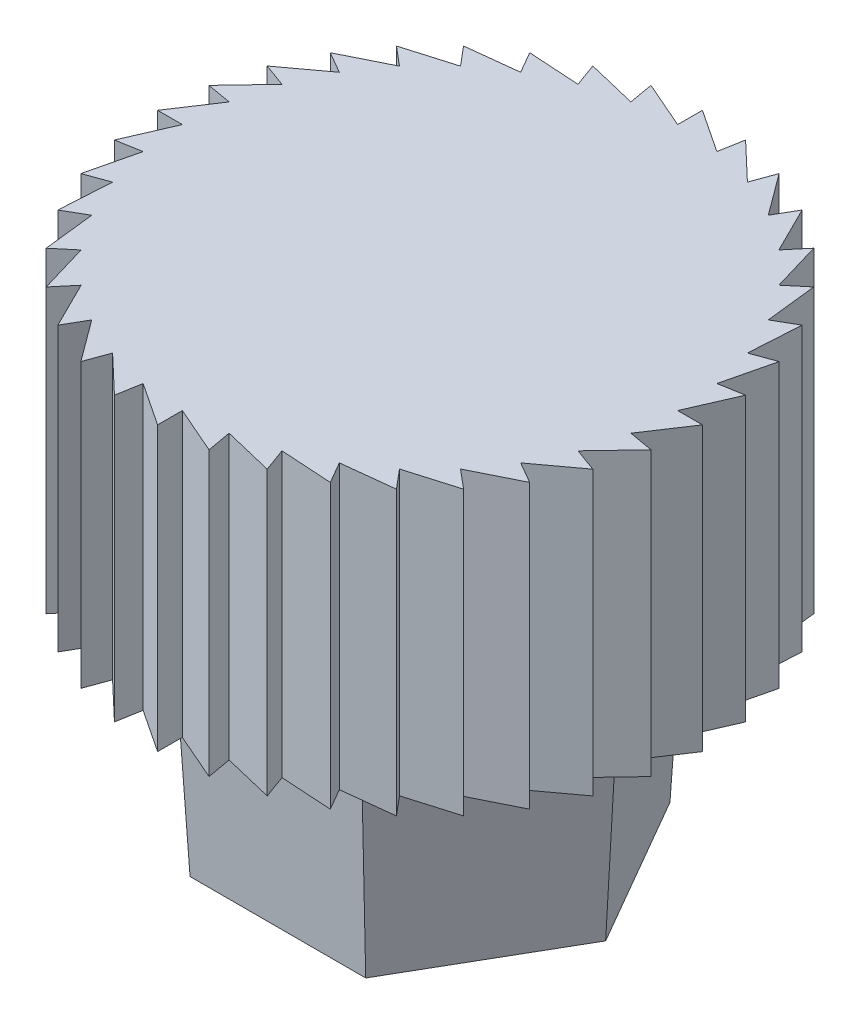
SolidWorks part; units mm, degrees
ref_plane "Front Plane" through (0, 0, 0) normal (0, 0, 1) x (1, 0, 0)
ref_plane "Top Plane" through (0, 0, 0) normal (0, 1, 0) x (1, 0, 0)
ref_plane "Right Plane" through (0, 0, 0) normal (1, 0, 0) x (0, 0, -1)
sketch "Sketch1" plane through (0, 0, 0) normal (0, 1, 0) x (1, 0, 0)
  line L1 (2.4826, 0) -> (1.2413, 2.15)
  line L2 (1.2413, 2.15) -> (-1.2413, 2.15)
  line L3 (-1.2413, 2.15) -> (-2.4826, 0)
  line L4 (-2.4826, 0) -> (-1.2413, -2.15)
  line L5 (-1.2413, -2.15) -> (1.2413, -2.15)
  line L6 (1.2413, -2.15) -> (2.4826, 0)
  circle A0 centre (0, 0) radius 2.15 construction
ref_plane "Plane1" through (0, 3, 0) normal (0, 1, 0) x (1, 0, 0)
sketch "Sketch2" plane through (0, 3, 0) normal (0, 1, 0) x (1, 0, 0)
  line L1 (2.6558, 0) -> (1.3279, 2.3)
  line L2 (1.3279, 2.3) -> (-1.3279, 2.3)
  line L3 (-1.3279, 2.3) -> (-2.6558, 0)
  line L4 (-2.6558, 0) -> (-1.3279, -2.3)
  line L5 (-1.3279, -2.3) -> (1.3279, -2.3)
  line L6 (1.3279, -2.3) -> (2.6558, 0)
  circle A0 centre (0, 0) radius 2.3 construction
loft "Loft1" add profiles "Sketch1", "Sketch2"
sketch "Sketch3" plane through (0, 3, 0) normal (0, 1, 0) x (1, 0, 0)
  line L0 (0, 0) -> (0, 3.9809) construction
  line L2 (0, 0) -> (0.7188, 4.0763) construction
  line L4 (0, 3.5) -> (0, 3.85)
  line L5 (0, 3.85) -> (0.6078, 3.4468)
  line L149 (0.6078, 3.4468) -> (0.6685, 3.7915)
  line L150 (0.6685, 3.7915) -> (1.1971, 3.2889)
  line L151 (1.1971, 3.2889) -> (1.3168, 3.6178)
  line L152 (1.3168, 3.6178) -> (1.75, 3.0311)
  line L153 (1.75, 3.0311) -> (1.925, 3.3342)
  line L154 (1.925, 3.3342) -> (2.2498, 2.6812)
  line L155 (2.2498, 2.6812) -> (2.4747, 2.9493)
  line L156 (2.4747, 2.9493) -> (2.6812, 2.2498)
  line L157 (2.6812, 2.2498) -> (2.9493, 2.4747)
  line L158 (2.9493, 2.4747) -> (3.0311, 1.75)
  line L159 (3.0311, 1.75) -> (3.3342, 1.925)
  line L160 (3.3342, 1.925) -> (3.2889, 1.1971)
  line L161 (3.2889, 1.1971) -> (3.6178, 1.3168)
  line L162 (3.6178, 1.3168) -> (3.4468, 0.6078)
  line L163 (3.4468, 0.6078) -> (3.7915, 0.6685)
  line L164 (3.7915, 0.6685) -> (3.5, 0)
  line L165 (3.5, 0) -> (3.85, 0)
  line L166 (3.85, 0) -> (3.4468, -0.6078)
  line L167 (3.4468, -0.6078) -> (3.7915, -0.6685)
  line L168 (3.7915, -0.6685) -> (3.2889, -1.1971)
  line L169 (3.2889, -1.1971) -> (3.6178, -1.3168)
  line L170 (3.6178, -1.3168) -> (3.0311, -1.75)
  line L171 (3.0311, -1.75) -> (3.3342, -1.925)
  line L172 (3.3342, -1.925) -> (2.6812, -2.2498)
  line L173 (2.6812, -2.2498) -> (2.9493, -2.4747)
  line L174 (2.9493, -2.4747) -> (2.2498, -2.6812)
  line L175 (2.2498, -2.6812) -> (2.4747, -2.9493)
  line L176 (2.4747, -2.9493) -> (1.75, -3.0311)
  line L177 (1.75, -3.0311) -> (1.925, -3.3342)
  line L178 (1.925, -3.3342) -> (1.1971, -3.2889)
  line L179 (1.1971, -3.2889) -> (1.3168, -3.6178)
  line L180 (1.3168, -3.6178) -> (0.6078, -3.4468)
  line L181 (0.6078, -3.4468) -> (0.6685, -3.7915)
  line L182 (0.6685, -3.7915) -> (0, -3.5)
  line L183 (0, -3.5) -> (0, -3.85)
  line L184 (0, -3.85) -> (-0.6078, -3.4468)
  line L185 (-0.6078, -3.4468) -> (-0.6685, -3.7915)
  line L186 (-0.6685, -3.7915) -> (-1.1971, -3.2889)
  line L187 (-1.1971, -3.2889) -> (-1.3168, -3.6178)
  line L188 (-1.3168, -3.6178) -> (-1.75, -3.0311)
  line L189 (-1.75, -3.0311) -> (-1.925, -3.3342)
  line L190 (-1.925, -3.3342) -> (-2.2498, -2.6812)
  line L191 (-2.2498, -2.6812) -> (-2.4747, -2.9493)
  line L192 (-2.4747, -2.9493) -> (-2.6812, -2.2498)
  line L193 (-2.6812, -2.2498) -> (-2.9493, -2.4747)
  line L194 (-2.9493, -2.4747) -> (-3.0311, -1.75)
  line L195 (-3.0311, -1.75) -> (-3.3342, -1.925)
  line L196 (-3.3342, -1.925) -> (-3.2889, -1.1971)
  line L197 (-3.2889, -1.1971) -> (-3.6178, -1.3168)
  line L198 (-3.6178, -1.3168) -> (-3.4468, -0.6078)
  line L199 (-3.4468, -0.6078) -> (-3.7915, -0.6685)
  line L200 (-3.7915, -0.6685) -> (-3.5, 0)
  line L201 (-3.5, 0) -> (-3.85, 0)
  line L202 (-3.85, 0) -> (-3.4468, 0.6078)
  line L203 (-3.4468, 0.6078) -> (-3.7915, 0.6685)
  line L204 (-3.7915, 0.6685) -> (-3.2889, 1.1971)
  line L205 (-3.2889, 1.1971) -> (-3.6178, 1.3168)
  line L206 (-3.6178, 1.3168) -> (-3.0311, 1.75)
  line L207 (-3.0311, 1.75) -> (-3.3342, 1.925)
  line L208 (-3.3342, 1.925) -> (-2.6812, 2.2498)
  line L209 (-2.6812, 2.2498) -> (-2.9493, 2.4747)
  line L210 (-2.9493, 2.4747) -> (-2.2498, 2.6812)
  line L211 (-2.2498, 2.6812) -> (-2.4747, 2.9493)
  line L212 (-2.4747, 2.9493) -> (-1.75, 3.0311)
  line L213 (-1.75, 3.0311) -> (-1.925, 3.3342)
  line L214 (-1.925, 3.3342) -> (-1.1971, 3.2889)
  line L215 (-1.1971, 3.2889) -> (-1.3168, 3.6178)
  line L216 (-1.3168, 3.6178) -> (-0.6078, 3.4468)
  line L217 (-0.6078, 3.4468) -> (-0.6685, 3.7915)
  line L218 (-0.6685, 3.7915) -> (0, 3.5)
  circle A0 centre (0, 0) radius 3.5 construction
  dimension "D1" = 10
  dimension "D3" = 36
  dimension "D2" = 0.35
extrude "Boss-Extrude1" add sketch "Sketch3" along normal blind 4
